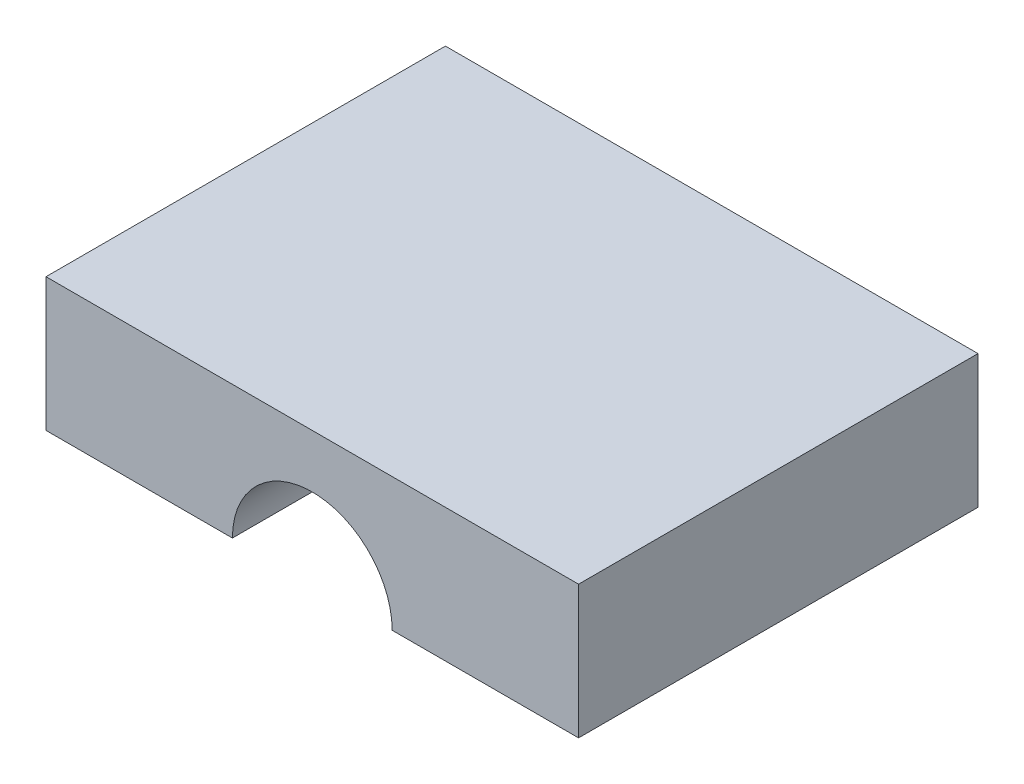
SolidWorks part; units mm, degrees
material "ABS"
ref_plane "前视基准面" through (0, 0, 0) normal (0, 0, 1) x (1, 0, 0)
ref_plane "上视基准面" through (0, 0, 0) normal (0, 1, 0) x (1, 0, 0)
ref_plane "右视基准面" through (0, 0, 0) normal (1, 0, 0) x (0, 0, -1)
other "Configuration Table"
sketch "草图1" plane through (0, 0, 0) normal (0, 1, 0) x (1, 0, 0)
  line L1 (0, 0) -> (40, 0)
  line L2 (0, 0) -> (0, 30)
  line L3 (0, 30) -> (40, 30)
  line L4 (40, 0) -> (40, 30)
  dimension "D1" = 30
  dimension "D2" = 40
extrude "凸台-拉伸1" add sketch "草图1" along normal blind 10
sketch "草图2" plane through (0, 0, 0) normal (0, 0, 1) x (1, 0, 0)
  line L0 (0, 0) -> (40, 0) construction
  line L1 (14, 0) -> (26, 0)
  arc A0 (14, 0) -> (26, 0) centre (20, 0) cw
  dimension "D1" = 6
extrude "切除-拉伸1" cut sketch "草图2" against normal through all
